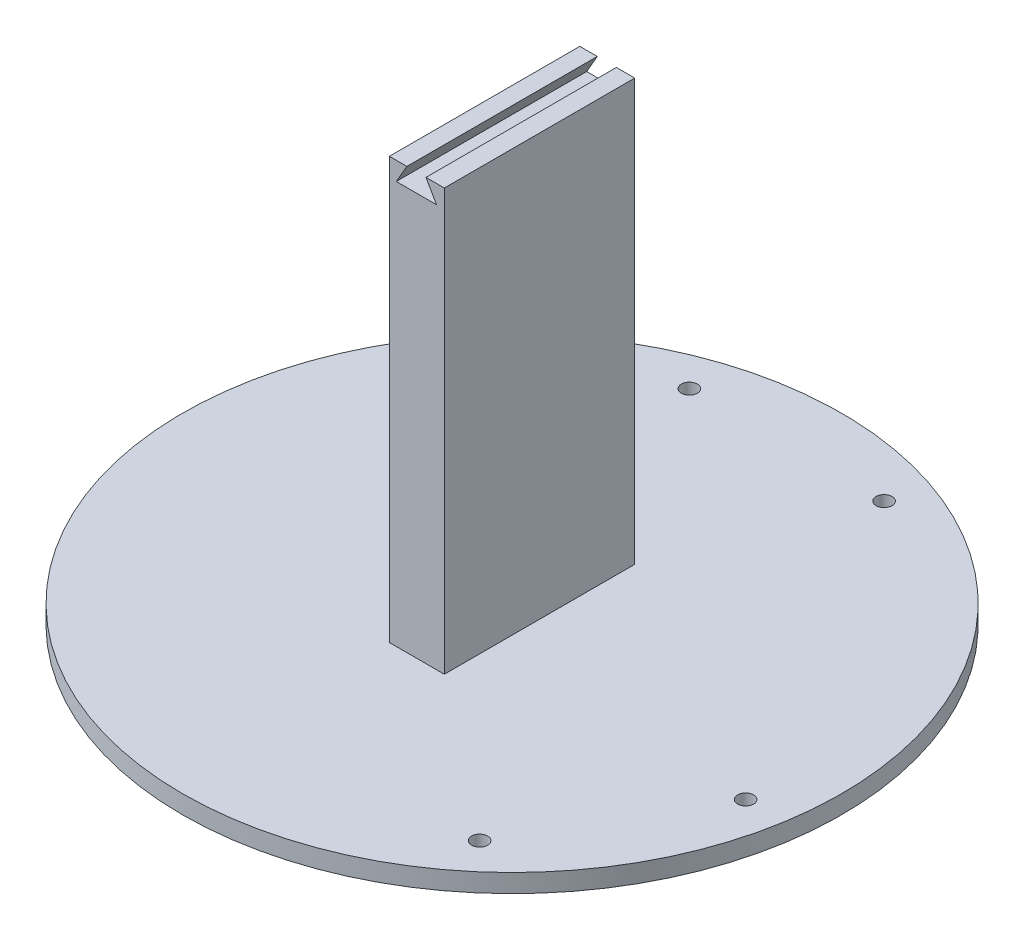
SolidWorks part; units mm, degrees
ref_plane "Front Plane" through (0, 0, 0) normal (0, 0, 1) x (1, 0, 0)
ref_plane "Top Plane" through (0, 0, 0) normal (0, 1, 0) x (1, 0, 0)
ref_plane "Right Plane" through (0, 0, 0) normal (1, 0, 0) x (0, 0, -1)
sketch "Sketch1" plane through (0, 0, 0) normal (0, 1, 0) x (1, 0, 0)
  circle A0 centre (0, 0) radius 90
  dimension "D1" = 180
extrude "Boss-Extrude2" add sketch "Sketch1" along normal blind 5
sketch "Sketch3" plane through (0, 0, 0) normal (0, 1, 0) x (1, 0, 0)
  line L1 (-7.5, 26) -> (7.5, 26)
  line L2 (-7.5, 26) -> (-7.5, -26)
  line L3 (-7.5, -26) -> (7.5, -26)
  line L4 (7.5, 26) -> (7.5, -26)
  line L5 (-7.5, 26) -> (7.5, -26) construction
  line L6 (-7.5, -26) -> (7.5, 26) construction
  point P0 (0, 0)
  dimension "D1" = 15
  dimension "D2" = 52
extrude "Boss-Extrude3" add sketch "Sketch3" along normal blind 120
sketch "Sketch5" plane through (0, 0, 26) normal (0, 0, 1) x (1, 0, 0)
  line L0 (0, 89.2928) -> (0, -14.5542) construction
  line L1 (-5.6191, 114.98) -> (-2.7208, 120)
  line L2 (-5.6191, 114.98) -> (5.3809, 114.98)
  line L3 (-7.5, 120) -> (7.5, 120) construction
  line L4 (5.3809, 114.98) -> (2.4826, 120)
  line L5 (2.4826, 120) -> (-2.7208, 120)
  point P3 (-0.1191, 120)
  dimension "D1" = 5.02
  dimension "D2" = 120
  dimension "D3" = 120
  dimension "D4" = 11
extrude "Cut-Extrude1" cut sketch "Sketch5" against normal blind 80
sketch "Sketch8" plane through (0, 0, 0) normal (0, -1, 0) x (1, 0, 0)
  line L0 (-54.1768, 0) -> (59.6574, 0) construction
  line L1 (0, 51.6162) -> (0, -53.9522) construction
  line L2 (0, 0) -> (64.9519, 37.5)
  line L3 (-75, 0) -> (0, 0)
  line L4 (0, 0) -> (0, -42.5)
  line L7 (26.5869, -75) -> (-26.5869, -75)
  line L8 (51.6594, 60.5233) -> (78.2444, 14.4767)
  circle A3 centre (0, 0) radius 75
  circle A5 centre (26.5869, -75) radius 2.1825
  circle A7 centre (-26.5869, -75) radius 2.1826
  circle A10 centre (51.6594, 60.5233) radius 2.1825
  circle A11 centre (78.2444, 14.4767) radius 2.1825
  arc A12 (-75, 0) -> (-64.9519, 37.5) centre (0, 0) cw
  point P14 (-75, 0)
  point P17 (0, -75)
  point P19 (-36.8061, 21.25)
  point P24 (64.9519, 37.5)
  dimension "D2" = 53.1737
  dimension "D6" = 4.365
  dimension "D7" = 4.365
  dimension "D8" = 150
  dimension "D10" = 53.17
extrude "Cut-Extrude3" cut sketch "Sketch8" against normal blind 80
